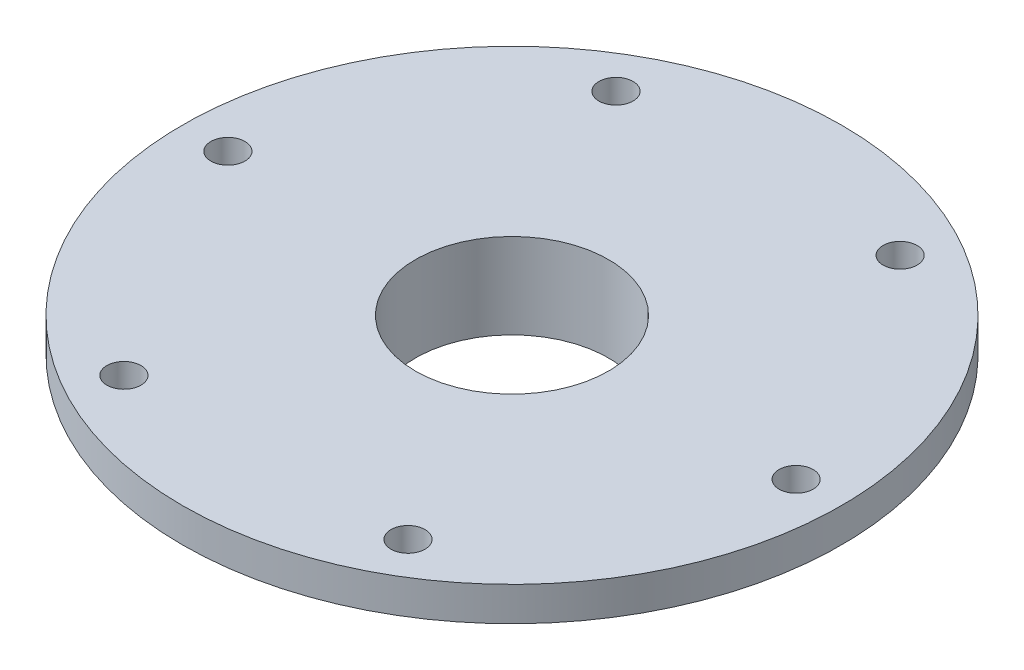
SolidWorks part; units mm, degrees
material "1060 Alloy"
ref_plane "Front Plane" through (0, 0, 0) normal (0, 0, 1) x (1, 0, 0)
ref_plane "Top Plane" through (0, 0, 0) normal (0, 1, 0) x (1, 0, 0)
ref_plane "Right Plane" through (0, 0, 0) normal (1, 0, 0) x (0, 0, -1)
sketch "Sketch4" plane through (0, 0, 0) normal (0, 0, 1) x (1, 0, 0)
  line L0 (0, 27.2792) -> (0, -44.2975) construction
  line L1 (-8.5, 0) -> (-29, 0)
  line L2 (-29, 0) -> (-29, -3)
  line L3 (-29, -3) -> (-11.75, -3)
  line L4 (-11.75, -3) -> (-11.75, -7.5)
  line L5 (-11.75, -7.5) -> (-8.5, -7.5)
  line L6 (-8.5, -7.5) -> (-8.5, 0)
  line L7 (0, 15) -> (-38, 15) construction
  line L8 (0, 20) -> (-12, 20) construction
  line L9 (-12, 20) -> (-38, 15) construction
  line L10 (-25, 17.5) -> (-25, 15) construction
  dimension "D2" = 3
  dimension "D3" = 8.5
  dimension "D4" = 11.75
  dimension "D5" = 4.5
  dimension "D6" = 15
  dimension "D7" = 38
  dimension "D8" = 12
  dimension "D9" = 5
  dimension "D1" = 29
revolve "Revolve1" add sketch "Sketch4" angle 360 about L0
sketch "Sketch5" plane through (0, 0, 0) normal (0, 1, 0) x (1, 0, 0)
  line L0 (-12, 0) -> (-38, 0) construction
  circle A0 centre (0, 0) radius 25 construction
  circle A1 centre (-25, 0) radius 1.5
  circle A2 centre (-12.5, 21.6506) radius 1.5
  circle A3 centre (12.5, 21.6506) radius 1.5
  circle A4 centre (25, 0) radius 1.5
  circle A5 centre (12.5, -21.6506) radius 1.5
  circle A6 centre (-12.5, -21.6506) radius 1.5
  circle A7 centre (0, 0) radius 12 construction
  circle A9 centre (0, 0) radius 38 construction
  point P17 (0, 0)
  dimension "D2" = 3
  dimension "D3" = 24
  dimension "D4" = 76
  dimension "D1" = 6
extrude "Cut-Extrude1" cut sketch "Sketch5" against normal through all
equation "\"Stator_OD\"= 60'No Tolerance given"
equation "\"A\"=35.81 'taken off spec sheet for 06808 (A)"
equation "\"Rotor_ID\"= 30'No Tolerance Given"
equation "\"back_bearing_Thickness\"= 5'-0.12"
equation "\"back_bearing_OD\"= 24'-0.009 https://www.mcmaster.com/5972K155/"
equation "\"Stator_Gap\"= 0.0375'+- 0.0125 (From 1.3.3.1 Kollmorgen manual)"
equation "\"Back_mount_hole\"= 1.75'To be tapped to M2 (USE LOCKTITE)"
equation "\"facePlate_Mount_Hole\"= 2.75'To be tapped to M3"
equation "\"final_shaftD\"= 12'To fit in harmonic"
equation "\"final_shaftL\"= 5.25+3+\"sheet_thick\"+\"connector_thick\"-3+\"harmon_coupleL\"+0.5-\"shaft_Ladjust\"'length to make everything nice and aligned"
equation "\"back_bearing_ID\"= 15'"
equation "\"back_bearing_IDOD\"= 16.5'measured off CAD, actually 16.75, but rounded down to nicer number"
equation "\"rotor_shaftD\"= \"Rotor_ID\" - (\"rotor-shaft_gap\")*2'"
equation "\"front_bearing_ID\"= 12'https://www.mcmaster.com/5972K154/"
equation "\"front_bearing_OD\"= 21'-0.009"
equation "\"front_bearing_IDOD\"= 13.5'Measured off CAD. Actually 13.75, but rounded down"
equation "\"front_bearing_Thickness\"= 5'-0.12"
equation "\"rotor_thickness\"= 2.4'measured off CAD"
equation "\"rotor_height\"= 32.86'+-0.075 taken off spec sheet for 06826 (C)"
equation "\"B\"= 26.3'+-0.35 taken off spec sheet for 06826"
equation "\"D3@Sketch4\" = \"back_bearing_ID\" / 2 + 1"
equation "\"D4@Sketch4\"=\"back_bearing_OD\"/2-0.25"
equation "\"D3@Sketch5\"=\"back_bearing_OD\""
equation "\"D4@Sketch5\"=\"Stator_OD\"+16"
equation "\"D7@Sketch4\" = \"Stator_OD\" / 2 + 8"
equation "\"D8@Sketch4\"=\"back_bearing_OD\"/2"
equation "\"D2@Sketch5\"=\"facePlate_Mount_Hole\"+0.25"
equation "\"rotor-shaft_gap\" = 0.0185 '+-0.0065 (from manual)"
equation "\"key_L\"= 20'-0.2 https://www.mcmaster.com/2977N19/"
equation "\"key_H\"= 4'-0.03"
equation "\"key_W\"= 4'-0.03"
equation "\"harmon_keyH\"= 13.8'+0.1 from drawing"
equation "\"harmon_coupleL\"= 21.5' taken from drawing https://www.harmonicdrive.net/_hd/content/caddownloads/dxf/csg-2uh-lw_gearheads/csg-20-100-2uh-lw.pdf"
equation "\"harmon_diam\"= 93' from drawing"
equation "\"harmon_BCD\"= 82' from drawing"
equation "\"harmon_holeD1\"= 5.5' from drawing"
equation "\"harmon_holeD2\"= 5' from drawing"
equation "\"harmon_holeAng\"= 22.5' from drawing"
equation "\"sheet_thick\"= 1/8*25.4 'random, replace w actual sheet thickness when u feel like :)"
equation "\"nut-thickness\"= 5 'idk measure the ones in the shop and adjust"
equation "\"connector_thick\"= 10' random for now"
equation "\"shaft_Ladjust\"= 6.5' sorry. It's silly, but it works."
